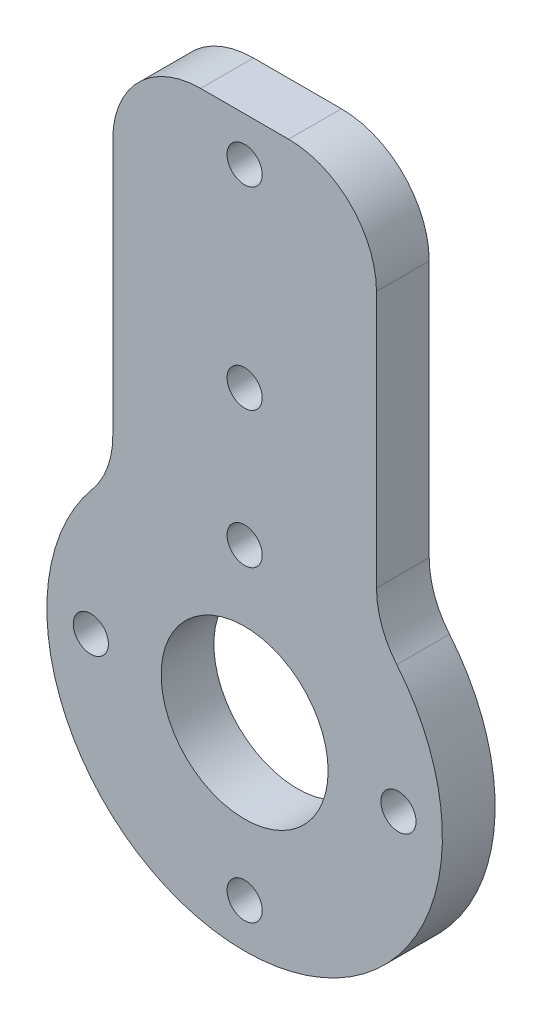
SolidWorks part; units mm, degrees
ref_plane "Front Plane" through (0, 0, 0) normal (0, 0, 1) x (1, 0, 0)
ref_plane "Top Plane" through (0, 0, 0) normal (0, 1, 0) x (1, 0, 0)
ref_plane "Right Plane" through (0, 0, 0) normal (1, 0, 0) x (0, 0, -1)
sketch "Sketch1" plane through (0, 0, 0) normal (0, 0, 1) x (1, 0, 0)
  line L0 (-15, 60) -> (15, 60)
  line L3 (-15, 60) -> (-15, 16.7705)
  line L4 (15, 60) -> (15, 16.7705)
  circle A0 centre (0, 0) radius 22.5
  circle A1 centre (0, 0) radius 9.5
  circle A2 centre (0, 17.5) radius 2
  circle A3 centre (17.5, 0) radius 2
  circle A4 centre (0, -17.5) radius 2
  circle A5 centre (-17.5, 0) radius 2
  circle A6 centre (0, 55) radius 2
  circle A7 centre (0, 33) radius 2
  point P10 (0, 60)
  point P17 (0, 0)
  dimension "D1" = 45
  dimension "D3" = 19
  dimension "D4" = 4
  dimension "D8" = 4
  dimension "D9" = 4
  dimension "D2" = 60
  dimension "D5" = 17.5
  dimension "D7" = 30
  dimension "D10" = 5
  dimension "D11" = 22
  dimension "D6" = 4
extrude "Boss-Extrude1" add sketch "Sketch1" along normal mid plane 6 contours A0 L4 L0 L3 | A0 A5 A4 A3 A2 A1
fillet "Fillet1" radius 10 4 edges at (15, 60, 0) (-15, 60, 0) (15, 16.7705, 0) (-15, 16.7705, 0)
